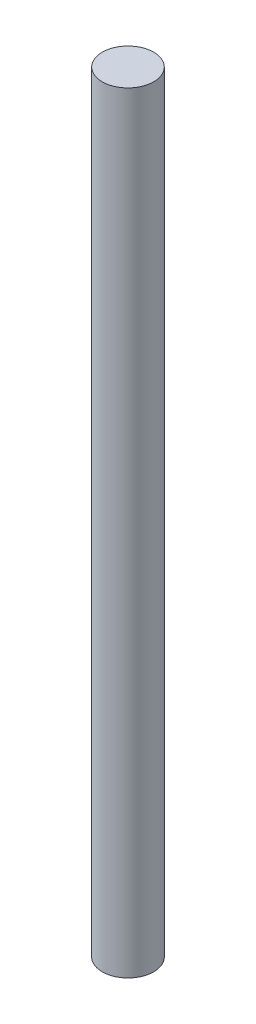
SolidWorks part; units mm, degrees
ref_plane "Front Plane" through (0, 0, 0) normal (0, 0, 1) x (1, 0, 0)
ref_plane "Top Plane" through (0, 0, 0) normal (0, 1, 0) x (1, 0, 0)
ref_plane "Right Plane" through (0, 0, 0) normal (1, 0, 0) x (0, 0, -1)
sketch "Sketch1" plane through (0, 0, 0) normal (0, 1, 0) x (1, 0, 0)
  circle A0 centre (0, 0) radius 1
  dimension "D1" = 2
extrude "Boss-Extrude1" add sketch "Sketch1" along normal blind 30
